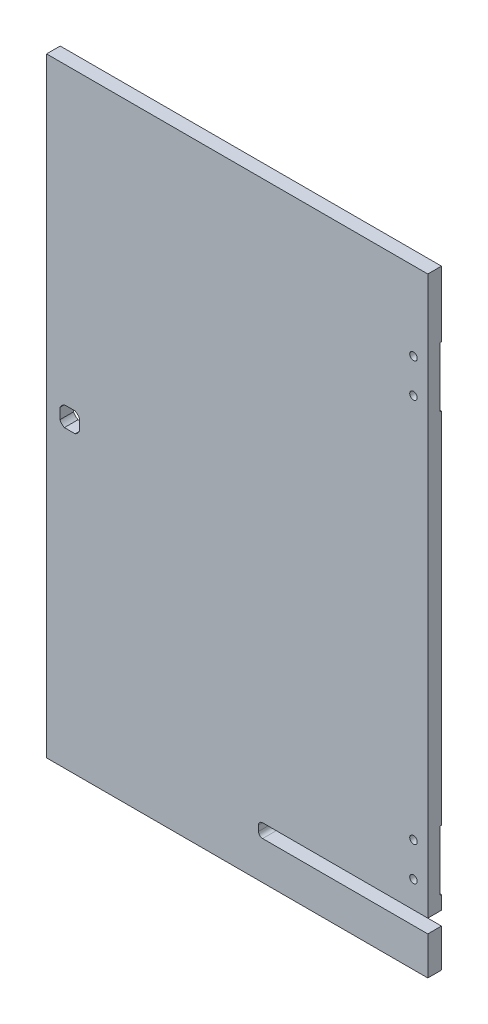
SolidWorks part; units mm, degrees
material "Oak"
ref_plane "Front Plane" through (0, 0, 0) normal (0, 0, 1) x (1, 0, 0)
ref_plane "Top Plane" through (0, 0, 0) normal (0, 1, 0) x (1, 0, 0)
ref_plane "Right Plane" through (0, 0, 0) normal (1, 0, 0) x (0, 0, -1)
sketch "Sketch1" plane through (0, 0, 0) normal (0, 0, 1) x (1, 0, 0)
  line L1 (-139.75, 223.5) -> (139.75, 223.5)
  line L2 (-139.75, 223.5) -> (-139.75, -223.5)
  line L3 (-139.75, -223.5) -> (139.75, -223.5)
  line L4 (139.75, 223.5) -> (139.75, -223.5)
  line L5 (-139.75, 223.5) -> (139.75, -223.5) construction
  line L6 (-139.75, -223.5) -> (139.75, 223.5) construction
  point P0 (0, 0)
  dimension "D1" = 279.5
  dimension "D2" = 447
extrude "Boss-Extrude1" add sketch "Sketch1" along normal blind 10
sketch "Sketch2" plane through (0, 0, 0) normal (0, 0, -1) x (-1, 0, 0)
  line L0 (-139.75, -223.5) -> (-139.75, 223.5) construction
  line L1 (-139.75, 175.5) -> (-121.75, 175.5)
  line L2 (-139.75, 175.5) -> (-139.75, 131.5)
  line L3 (-139.75, 131.5) -> (-121.75, 131.5)
  line L4 (-118.75, 172.5) -> (-118.75, 134.5)
  line L5 (-120.75, -133.5) -> (-140.75, -133.5) construction
  line L6 (-139.75, -131.5) -> (-121.75, -131.5)
  line L7 (-139.75, -131.5) -> (-139.75, -175.5)
  line L8 (-139.75, -175.5) -> (-121.75, -175.5)
  line L9 (-118.75, -134.5) -> (-118.75, -172.5)
  line L10 (-120.75, -173.5) -> (-140.75, -173.5) construction
  line L11 (-120.75, -173.5) -> (-120.75, -133.5) construction
  line L12 (-120.75, 173.5) -> (-140.75, 173.5) construction
  line L13 (-120.75, 133.5) -> (-140.75, 133.5) construction
  line L14 (-120.75, 133.5) -> (-120.75, 173.5) construction
  arc A0 (-121.75, -175.5) -> (-118.75, -172.5) centre (-121.75, -172.5) ccw
  arc A1 (-121.75, -131.5) -> (-118.75, -134.5) centre (-121.75, -134.5) cw
  arc A2 (-121.75, 131.5) -> (-118.75, 134.5) centre (-121.75, 134.5) ccw
  arc A3 (-121.75, 175.5) -> (-118.75, 172.5) centre (-121.75, 172.5) cw
  dimension "D7" = 3
  dimension "D1" = 2
  dimension "D2" = 2
  dimension "D3" = 2
  dimension "D4" = 2
  dimension "D5" = 2
  dimension "D6" = 2
extrude "Cut-Extrude1" cut sketch "Sketch2" against normal blind 1
sketch "Sketch3" plane through (0, 0, 1) normal (0, 0, -1) x (-1, 0, 0)
  circle A0 centre (-129.25, 166) radius 2.75
  circle A1 centre (-129.25, 141) radius 2.75
  circle A2 centre (-129.25, -141) radius 2.75
  circle A3 centre (-129.25, -166) radius 2.75
  dimension "D1" = 5.5
extrude "Cut-Extrude2" cut sketch "Sketch3" against normal through all
sketch "Sketch4" plane through (0, 0, 0) normal (0, 0, -1) x (-1, 0, 0)
  line L0 (-190.6472, -188.5) -> (-190.6472, -192.5) construction
  line L1 (-140.75, -185.5) -> (-18.6472, -185.5)
  line L2 (-140.75, -185.5) -> (-140.75, -195.5)
  line L3 (-140.75, -195.5) -> (-18.6472, -195.5)
  line L4 (-15.6472, -188.5) -> (-15.6472, -192.5)
  arc A0 (-18.6472, -195.5) -> (-15.6472, -192.5) centre (-18.6472, -192.5) ccw
  arc A1 (-18.6472, -185.5) -> (-15.6472, -188.5) centre (-18.6472, -188.5) cw
  dimension "D2" = 3
  dimension "D1" = 175
extrude "Cut-Extrude3" cut sketch "Sketch4" against normal through all
sketch "Sketch5" plane through (0, 0, 10) normal (0, 0, 1) x (1, 0, 0)
  line L1 (-130, 7.25) -> (-115.5, 7.25)
  line L2 (-130, 7.25) -> (-130, -7.25)
  line L3 (-130, -7.25) -> (-115.5, -7.25)
  line L4 (-115.5, 7.25) -> (-115.5, -7.25)
  line L5 (-130, 7.25) -> (-115.5, -7.25) construction
  line L6 (-130, -7.25) -> (-115.5, 7.25) construction
  circle A0 centre (-122.75, 0) radius 8.25
  dimension "D1" = 16.5
  dimension "D2" = 14.5
extrude "Cut-Extrude4" cut sketch "Sketch5" against normal through all contours L4 A0 L1 L2 L3
